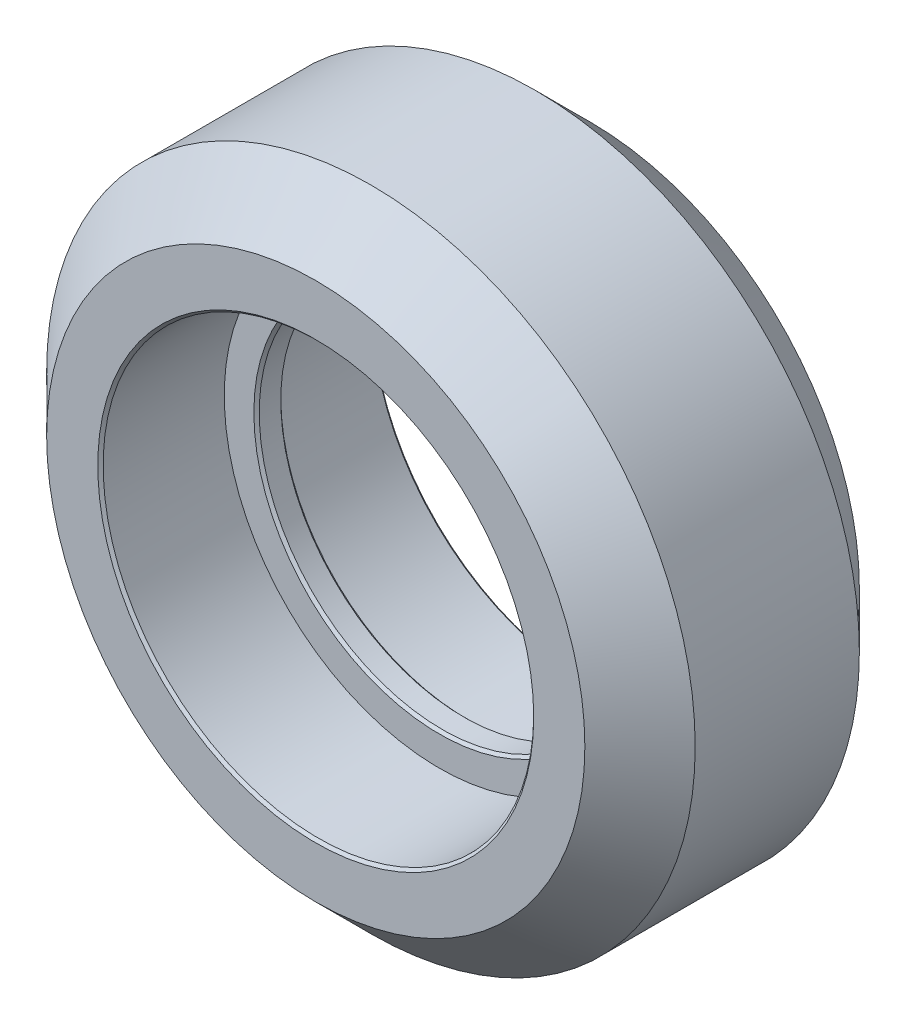
SolidWorks part; units mm, degrees
ref_plane "Alzado" through (0, 0, 0) normal (0, 0, 1) x (1, 0, 0)
ref_plane "Planta" through (0, 0, 0) normal (0, 1, 0) x (1, 0, 0)
ref_plane "Vista lateral" through (0, 0, 0) normal (1, 0, 0) x (0, 0, -1)
ref_plane "Plano1" through (0, -35.5, 0) normal (0, 1, 0) x (1, 0, 0)
sketch "Croquis1" plane through (0, -35.5, 0) normal (0, 1, 0) x (1, 0, 0)
  line L0 (22.4, 13.95) -> (22.3, 13.85)
  line L1 (22.3, 13.85) -> (22.3, 13.05)
  line L2 (22.3, 13.05) -> (22.4, 12.95)
  line L3 (22.4, 12.95) -> (23.5, 12.95)
  line L4 (23.5, 12.95) -> (23.5, 8.45)
  line L5 (23.5, 8.45) -> (23.6, 8.35)
  line L6 (23.6, 8.35) -> (25.5, 8.35)
  line L7 (25.5, 8.35) -> (27.55, 10.4)
  line L8 (27.55, 10.4) -> (27.55, 16.5)
  line L9 (27.55, 16.5) -> (25.5, 18.55)
  line L10 (25.5, 18.55) -> (23.6, 18.55)
  line L11 (23.6, 18.55) -> (23.5, 18.45)
  line L12 (23.5, 18.45) -> (23.5, 13.95)
  line L13 (23.5, 13.95) -> (22.4, 13.95)
  line L14 (15.5, 18.55) -> (15.5, 8.35) construction
revolve "Revolución1" add sketch "Croquis1" angle 360 about L14
ref_plane "Plano2" through (0, 0, -13.45) normal (0, 0, 1) x (1, 0, 0)
